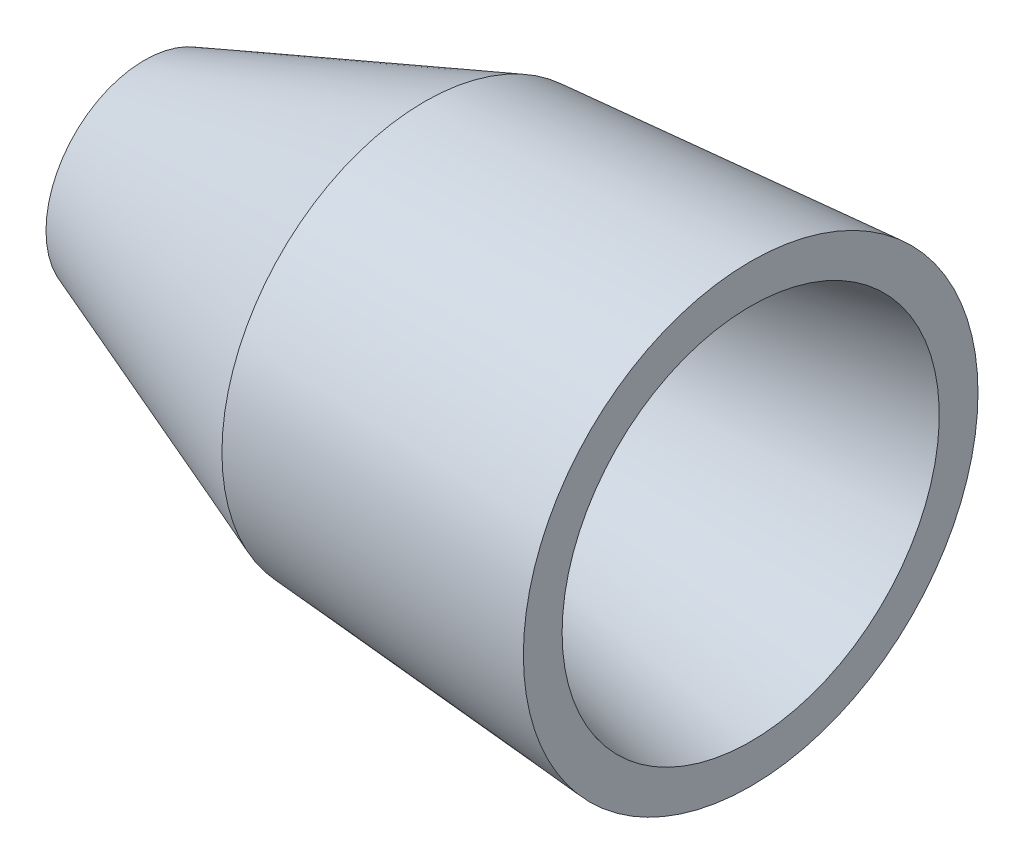
SolidWorks part; units mm, degrees
ref_plane "Front Plane" through (0, 0, 0) normal (0, 0, 1) x (1, 0, 0)
ref_plane "Top Plane" through (0, 0, 0) normal (0, 1, 0) x (1, 0, 0)
ref_plane "Right Plane" through (0, 0, 0) normal (1, 0, 0) x (0, 0, -1)
sketch "Sketch2" plane through (0, 0, 0) normal (0, 0, 1) x (1, 0, 0)
  line L2 (80, 30) -> (80, 0) construction
  line L3 (0, 0) -> (80, 0) construction
  line L4 (0, -1.0699) -> (72.8448, -1.0699) construction
  line L5 (0, 0) -> (0, 13) construction
  line L8 (0, 13) -> (0, 7.8884)
  line L9 (0, 7.8884) -> (80, 24.8884)
  line L10 (80, 24.8884) -> (80, 30)
  line L11 (0, 13) -> (36.9685, 26.7491)
  line L12 (36.9685, 26.7491) -> (80, 30)
  dimension "D2" = 80
  dimension "D3" = 30
  dimension "D6" = 13
revolve "Revolve5" add sketch "Sketch2" angle 360 about L3
sketch "Sketch6" plane through (0, 0, 0) normal (-1, 0, 0) x (0, 0, 1)
  circle A0 centre (0, 0) radius 13
  dimension "D1" = 26
extrude "Boss-Extrude1" add sketch "Sketch6" against normal blind 10
sketch "Sketch7" plane through (0, 0, 0) normal (-1, 0, 0) x (0, 0, 1)
  circle A0 centre (0, 8) radius 1.5
  circle A1 centre (0, -8) radius 1.5
  circle A2 centre (8, 0) radius 1.5
  circle A3 centre (-8, 0) radius 1.5
  circle A4 centre (0, 0) radius 13 construction
  dimension "D5" = 3
  dimension "D6" = 3
  dimension "D7" = 3
  dimension "D8" = 3
  dimension "D1" = 5
  dimension "D2" = 5
  dimension "D3" = 5
  dimension "D4" = 5
extrude "Cut-Extrude1" cut sketch "Sketch7" against normal blind 10
